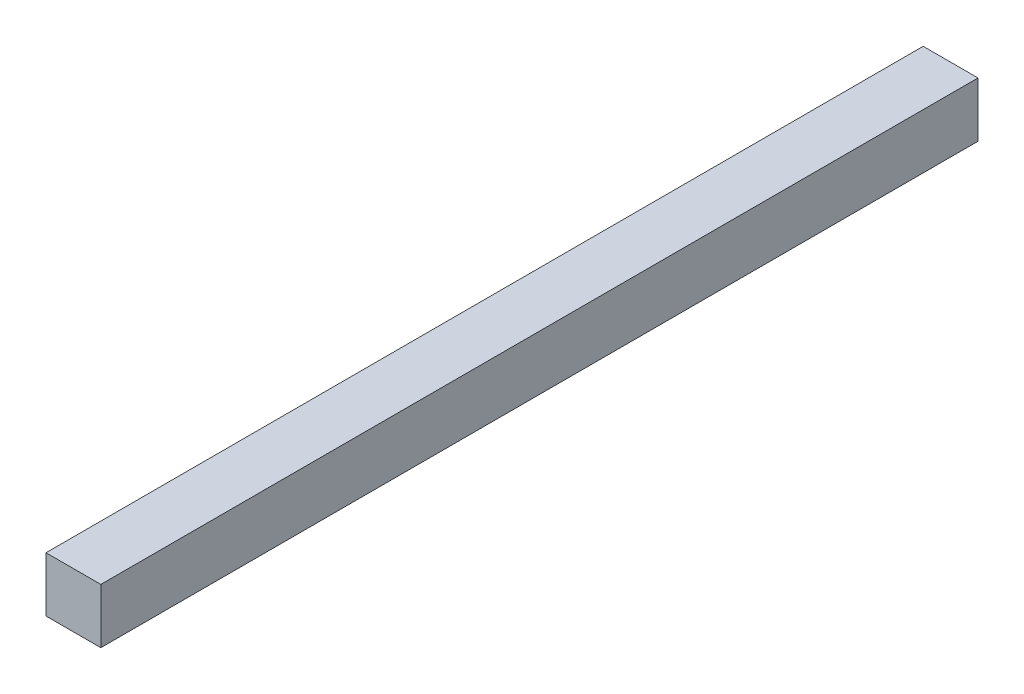
SolidWorks part; units mm, degrees
material "AISI 1045 Steel, cold drawn"
ref_plane "Front Plane" through (0, 0, 0) normal (0, 0, 1) x (1, 0, 0)
ref_plane "Top Plane" through (0, 0, 0) normal (0, 1, 0) x (1, 0, 0)
ref_plane "Right Plane" through (0, 0, 0) normal (1, 0, 0) x (0, 0, -1)
sketch "Sketch1" plane through (0, 0, 0) normal (0, 0, 1) x (1, 0, 0)
  line L1 (2.3813, -2.3813) -> (-2.3812, -2.3813)
  line L2 (2.3813, -2.3813) -> (2.3813, 2.3813)
  line L3 (2.3813, 2.3813) -> (-2.3812, 2.3812)
  line L4 (-2.3812, -2.3813) -> (-2.3812, 2.3812)
  line L5 (2.3813, -2.3813) -> (-2.3812, 2.3812) construction
  line L6 (2.3813, 2.3813) -> (-2.3812, -2.3813) construction
  point P0 (0, 0)
  dimension "D1" = 4.7625
  dimension "D2" = 4.7625
extrude "Boss-Extrude1" add sketch "Sketch1" along normal blind 76.2
